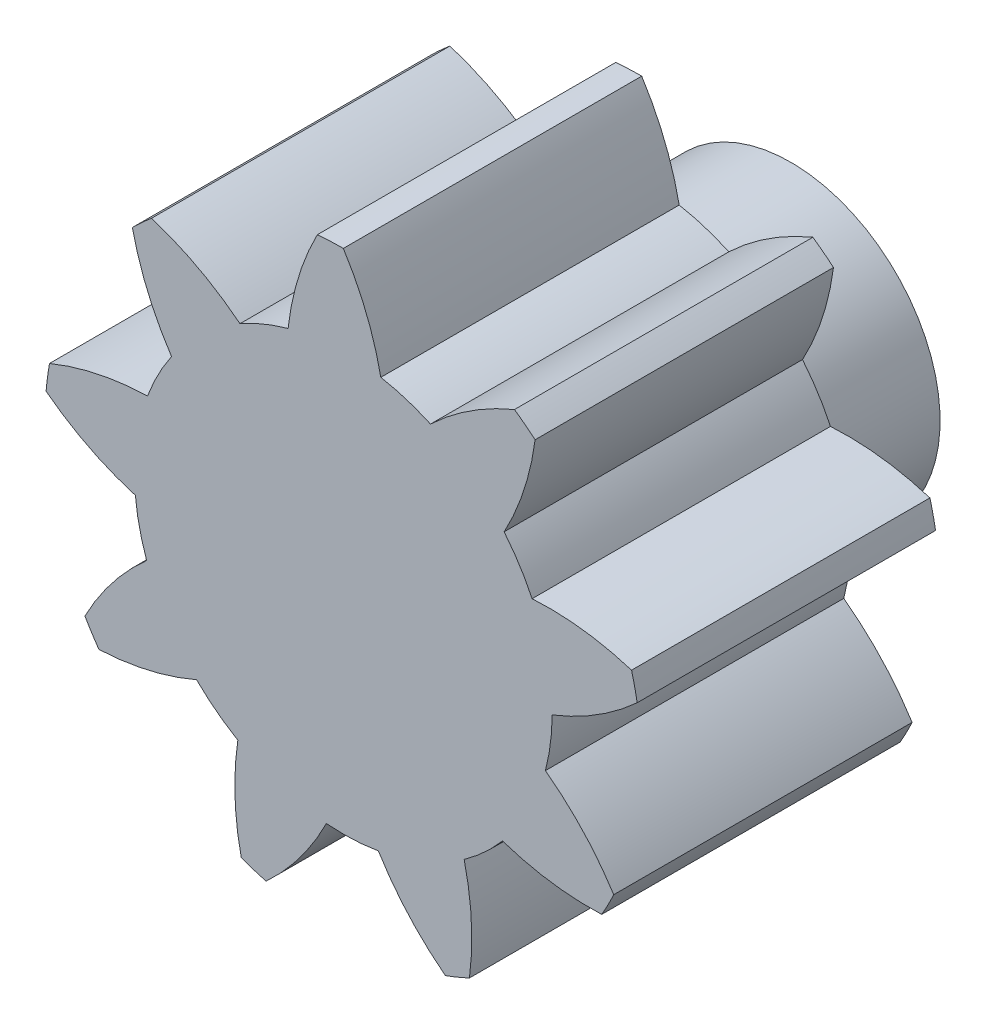
SolidWorks part; units mm, degrees
ref_plane "Plan de face" through (0, 0, 0) normal (0, 0, 1) x (1, 0, 0)
ref_plane "Plan de dessus" through (0, 0, 0) normal (0, 1, 0) x (1, 0, 0)
ref_plane "Plan de droite" through (0, 0, 0) normal (1, 0, 0) x (0, 0, -1)
sketch "Esquisse1" plane through (0, 0, 0) normal (0, 0, 1) x (1, 0, 0)
  circle A0 centre (0, 0) radius 10
  dimension "D1" = 20
extrude "Boss.-Extru.1" add sketch "Esquisse1" along normal blind 10
sketch "Esquisse2" plane through (0, 0, 0) normal (0, 0, -1) x (-1, 0, 0)
  circle A0 centre (0, 0) radius 5
  dimension "D1" = 10
extrude "Boss.-Extru.2" add sketch "Esquisse2" along normal blind 5
sketch "Esquisse3" plane through (0, 0, -5) normal (0, 0, -1) x (-1, 0, 0)
  circle A0 centre (0, 0) radius 2.5
  dimension "D1" = 5
extrude "Enlèv. mat.-Extru.2" cut sketch "Esquisse3" against normal blind 5
sketch "Esquisse5" plane through (0, 0, 10) normal (0, 0, 1) x (1, 0, 0)
  line L0 (0, 0) -> (0, 10) construction
  line L1 (0, 0) -> (5.7358, 8.1915) construction
  line L2 (3.0071, 9.5372) -> (0, 0) construction
  circle A0 centre (0, 0) radius 8.5 construction
  circle A1 centre (0, 0) radius 10 construction
  circle A2 centre (0, 0) radius 7 construction
  arc A6 (1.2563, 6.8863) -> (2.922, 6.361) centre (0, 0) cw
  arc A7 (0, 10) -> (5.7358, 8.1915) centre (0, 0) cw
  arc A8 (1.2563, 6.8863) -> (0, 10) centre (-7.7598, 5.0588) ccw
  arc A9 (2.9207, 6.3615) -> (5.7358, 8.1915) centre (9.2581, -0.3069) cw
  circle M1 centre (0, 0) radius 10
  dimension "D1" = 1.5
  dimension "D2" = 3
  dimension "D3" = 9.2632
  dimension "D5" = 9.2581
  dimension "D4" = 17.5
extrude "Enlèv. mat.-Extru.4" cut sketch "Esquisse5" against normal blind 10 contours A6 A9 A8 M1
pattern_circular "Répétition circulaire2" count 9 over 360 about axis through (0, 0, 0) along (0, 0, 1) of "Enlèv. mat.-Extru.4"
